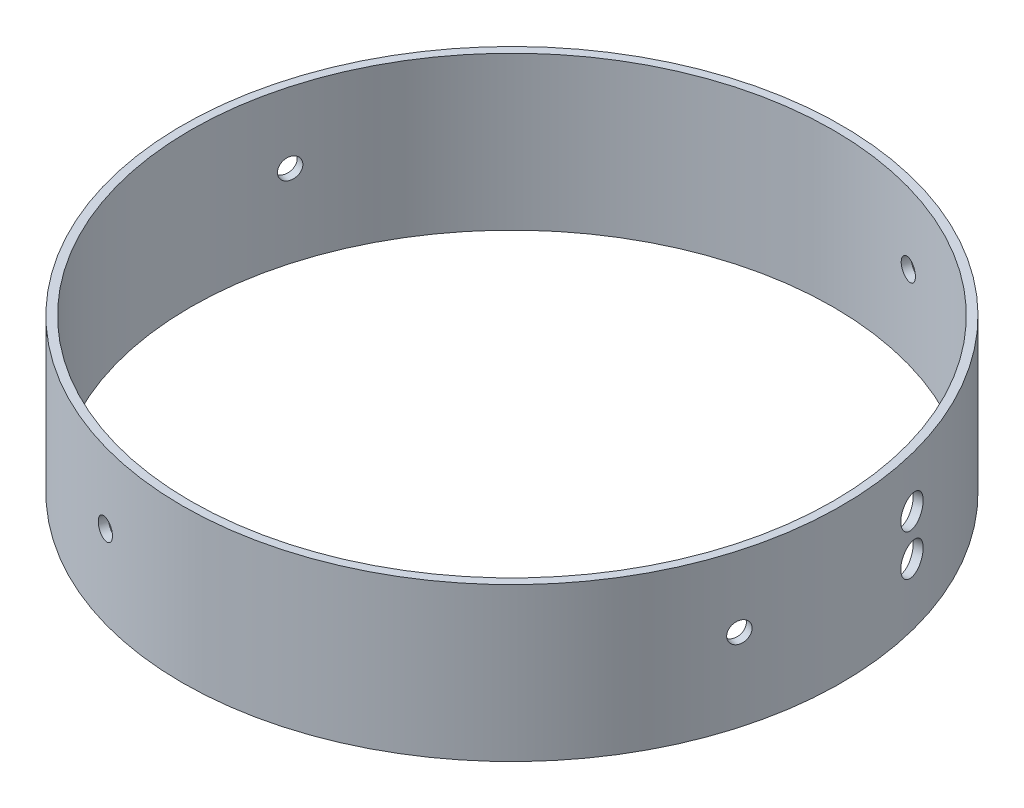
SolidWorks part; units mm, degrees
material "Wildman Fiberglass"
ref_plane "Front Plane" through (0, 0, 0) normal (0, 0, 1) x (1, 0, 0)
ref_plane "Top Plane" through (0, 0, 0) normal (0, 1, 0) x (1, 0, 0)
ref_plane "Right Plane" through (0, 0, 0) normal (1, 0, 0) x (0, 0, -1)
sketch "Sketch1" plane through (0, 0, 0) normal (0, 1, 0) x (1, 0, 0)
  circle A0 centre (0, 0) radius 49.53
  circle A1 centre (0, 0) radius 50.8
  dimension "D1" = 101.6
  dimension "D2" = 99.06
extrude "Boss-Extrude1" add sketch "Sketch1" along normal blind 23.622
extrude "Cut-Extrude1" cut sketch "Sketch2" against normal blind 25.4
sketch "Sketch2" plane through (80.7093, 206.3332, 111.646) normal (0.9693, 0, -0.2457) x (0, -1, 0)
  circle A0 centre (196.8082, 128.0554) radius 2.3813
  circle A1 centre (190.4582, 128.0554) radius 2.3813
extrude "Cut-Extrude2" cut sketch "Sketch3" against normal blind 37.338
sketch "Sketch3" plane through (-3.1003, 207.7782, 134.799) normal (-0.9623, 0, -0.2719) x (0, 1, 0)
  circle A0 centre (-195.0782, 130.5648) radius 1.5875
  point P3 (-80.7782, 130.5648)
  point P4 (-195.0782, 181.3648)
pattern_circular "CirPattern1" count 4 over 360 of "Cut-Extrude2"
equation "\"Length\"=0.93"
equation "\"D1@Boss-Extrude1\"=\"Length\""
